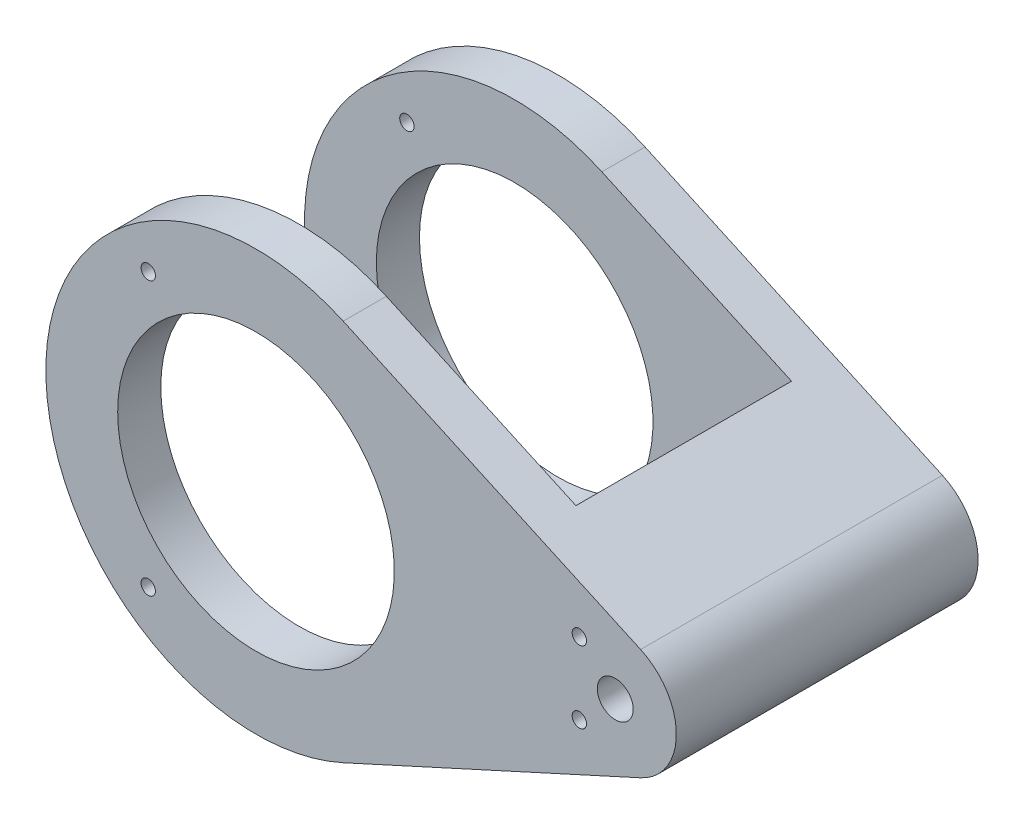
SolidWorks part; units mm, degrees
ref_plane "Face" through (0, 0, 0) normal (0, 0, 1) x (1, 0, 0)
ref_plane "Dessus" through (0, 0, 0) normal (0, 1, 0) x (1, 0, 0)
ref_plane "Droite" through (0, 0, 0) normal (1, 0, 0) x (0, 0, -1)
sketch "Esquisse1" plane through (0, 0, 0) normal (0, 0, 1) x (1, 0, 0)
  line L0 (50, 0) -> (0, 0) construction
  line L1 (12.1387, 26.6123) -> (53.5275, 7.7335)
  line L2 (-29.25, 0) -> (0, 0) construction
  line L3 (12.1388, -26.6123) -> (53.5275, -7.7335)
  line L4 (58.5, 0) -> (50, 0) construction
  circle A0 centre (0, 0) radius 19.25
  circle A1 centre (50, 0) radius 2.5
  arc A2 (12.1387, 26.6123) -> (12.1388, -26.6123) centre (0, 0) ccw
  arc A3 (53.5275, 7.7335) -> (53.5275, -7.7335) centre (50, 0) cw
  dimension "D1" = 38.5
  dimension "D2" = 5
  dimension "D4" = 10
  dimension "D5" = 6
  dimension "D3" = 50
extrude "Boss.-Extru.1" add sketch "Esquisse1" along normal blind 42
sketch "Esquisse2" plane through (5.2188, 0, 0) normal (0, 1, 0) x (1, 0, 0)
  line L0 (33.3087, -36) -> (-56.6913, -36)
  line L1 (-56.6913, -36) -> (-56.6913, -6)
  line L2 (48.3087, -21) -> (6.9199, -21) construction
  line L3 (48.3087, -42) -> (48.3087, 0) construction
  line L4 (6.9199, -42) -> (6.9199, 0) construction
  line L5 (48.3087, -42) -> (6.9199, -42) construction
  line L6 (33.3087, -36) -> (33.3087, -6)
  line L7 (33.3087, -6) -> (-56.6913, -6)
  point P13 (33.3087, -21)
  point P14 (-56.6913, -21)
  dimension "D1" = 6
  dimension "D2" = 90
  dimension "D3" = 15
extrude "Enlèv. mat.-Extru.1" cut sketch "Esquisse2" against normal through all both and the other way through all
sketch "Esquisse3" plane through (0, 0, 42) normal (0, 0, 1) x (1, 0, 0)
  line L0 (50, 0) -> (45, 0) construction
  line L1 (45, 0) -> (45, 5) construction
  line L2 (-15, 19) -> (-15, 0) construction
  line L3 (-15, 0) -> (50, 0) construction
  circle A0 centre (45, 5) radius 1
  circle A1 centre (45, -5) radius 1
  circle A2 centre (-15, 19) radius 1
  circle A3 centre (-15, -19) radius 1
  dimension "D1" = 2
  dimension "D2" = 5
  dimension "D3" = 5
  dimension "D4" = 65
  dimension "D5" = 19
extrude "Enlèv. mat.-Extru.2" cut sketch "Esquisse3" against normal up to vertex (42 mm away) up to point (53.5275, 7.7335, 0)
